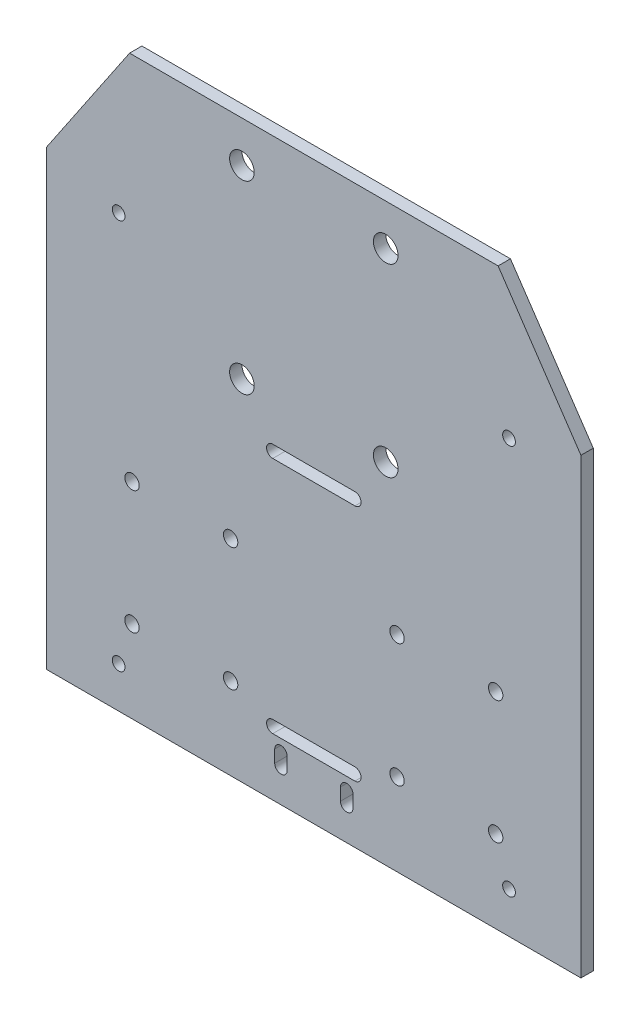
SolidWorks part; units mm, degrees
ref_plane "前视基准面" through (0, 0, 0) normal (0, 0, 1) x (1, 0, 0)
ref_plane "上视基准面" through (0, 0, 0) normal (0, 1, 0) x (1, 0, 0)
ref_plane "右视基准面" through (0, 0, 0) normal (1, 0, 0) x (0, 0, -1)
sketch "草图1" plane through (0, 0, 0) normal (0, 0, 1) x (1, 0, 0)
  line L0 (0, 0) -> (80.8163, 0) construction
  line L2 (65, -25) -> (65, 75.1634)
  line L4 (-65, -25) -> (-65, 75.1634)
  line L5 (22.0588, -25) -> (0, 0) construction
  line L6 (22.0588, 25) -> (-22.0588, -25) construction
  line L7 (0, 0) -> (0, -25) construction
  line L16 (-65, -25) -> (-65, -35)
  line L22 (-65, -35) -> (65, -35)
  line L23 (0, -25) -> (0, 105) construction
  line L24 (65, -35) -> (65, -25)
  line L26 (65, 75.1634) -> (44.8402, 105)
  line L27 (-65, 75.1634) -> (-44.8402, 105)
  line L29 (-44.8402, 105) -> (44.8402, 105)
  line L30 (-10, 38.5) -> (10, 38.5) construction
  line L31 (-10, 40) -> (10, 40)
  line L32 (-10, 37) -> (10, 37)
  line L33 (-10, -19.5) -> (10, -19.5) construction
  line L34 (-10, -18) -> (10, -18)
  line L35 (-10, -21) -> (10, -21)
  circle A0 centre (44.25, -15) radius 1.75
  circle A1 centre (20.25, -15) radius 1.75
  circle A2 centre (20.25, 15) radius 1.75
  circle A3 centre (44.25, 15) radius 1.75
  circle A4 centre (-44.25, 15) radius 1.75
  circle A5 centre (-20.25, 15) radius 1.75
  circle A6 centre (-20.25, -15) radius 1.75
  circle A7 centre (-44.25, -15) radius 1.75
  circle A20 centre (-17.5, 95) radius 3
  circle A21 centre (17.5, 95) radius 3
  circle A22 centre (-17.5, 50) radius 3
  circle A23 centre (17.5, 50) radius 3
  arc A24 (-10, 40) -> (-10, 37) centre (-10, 38.5) ccw
  arc A25 (10, 37) -> (10, 40) centre (10, 38.5) ccw
  arc A26 (-10, -18) -> (-10, -21) centre (-10, -19.5) ccw
  arc A27 (10, -21) -> (10, -18) centre (10, -19.5) ccw
  point P0 (0, 0)
  point P34 (0, 38.5)
  point P35 (0, 105)
  point P53 (0, -19.5)
  dimension "D3" = 3.5
  dimension "D4" = 20.75
  dimension "D8" = 6
  dimension "D9" = 35
  dimension "D11" = 10
  dimension "D16" = 1.5
  dimension "D17" = 10
  dimension "D2" = 140
  dimension "D5" = 130
  dimension "D12" = 20.75
  dimension "D13" = 20.75
  dimension "D14" = 20
  dimension "D15" = 17.5
  dimension "10" = 10
  dimension "D18" = 20
  dimension "D6" = 2
  dimension "D7" = 2
  dimension "D10" = 2
  dimension "D19" = 2
extrude "凸台-拉伸1" add sketch "草图1" along normal blind 3
sketch "草图3" plane through (0, 0, 0) normal (0, 0, -1) x (-1, 0, 0)
  line L4 (0, -28.2742) -> (0, 166.1841) construction
  line L6 (-8, -27) -> (-8, -24) construction
  line L7 (-9.52, -27) -> (-9.52, -24)
  line L8 (-6.48, -27) -> (-6.48, -24)
  line L9 (65, -35) -> (-65, -35) construction
  line L10 (8, -27) -> (8, -24) construction
  line L11 (9.52, -27) -> (9.52, -24)
  line L12 (6.48, -27) -> (6.48, -24)
  arc A5 (-9.52, -27) -> (-6.48, -27) centre (-8, -27) ccw
  arc A6 (-6.48, -24) -> (-9.52, -24) centre (-8, -24) ccw
  arc A7 (9.52, -27) -> (6.48, -27) centre (8, -27) cw
  arc A8 (6.48, -24) -> (9.52, -24) centre (8, -24) cw
  point P2 (-18, 97.8359)
  point P3 (-8, -25.5)
  point P13 (18, 97.8359)
  point P15 (8, -25.5)
  dimension "D1" = 1.52
  dimension "D3" = 8
  dimension "D2" = 8
  dimension "D4" = 3
extrude "切除-拉伸2" cut sketch "草图3" against normal blind 10
sketch "草图5" plane through (0, 0, 3) normal (0, 0, 1) x (1, 0, 0)
  line L0 (0, -35) -> (0, 63.5951) construction
  line L1 (44.8402, 105) -> (-44.8402, 105) construction
  line L3 (-65, -35) -> (65, -35) construction
  circle A0 centre (-47.5, 70) radius 1.55
  circle A1 centre (47.5, 70) radius 1.55
  circle A2 centre (-47.5, -25) radius 1.55
  circle A3 centre (47.5, -25) radius 1.55
  dimension "D1" = 3.1
  dimension "D2" = 47.5
  dimension "D3" = 2
  dimension "D4" = 130
  dimension "D5" = 95
  dimension "D6" = 47.5
  dimension "D7" = 95
  dimension "D8" = 10
extrude "切除-拉伸3" cut sketch "草图5" against normal blind 10
